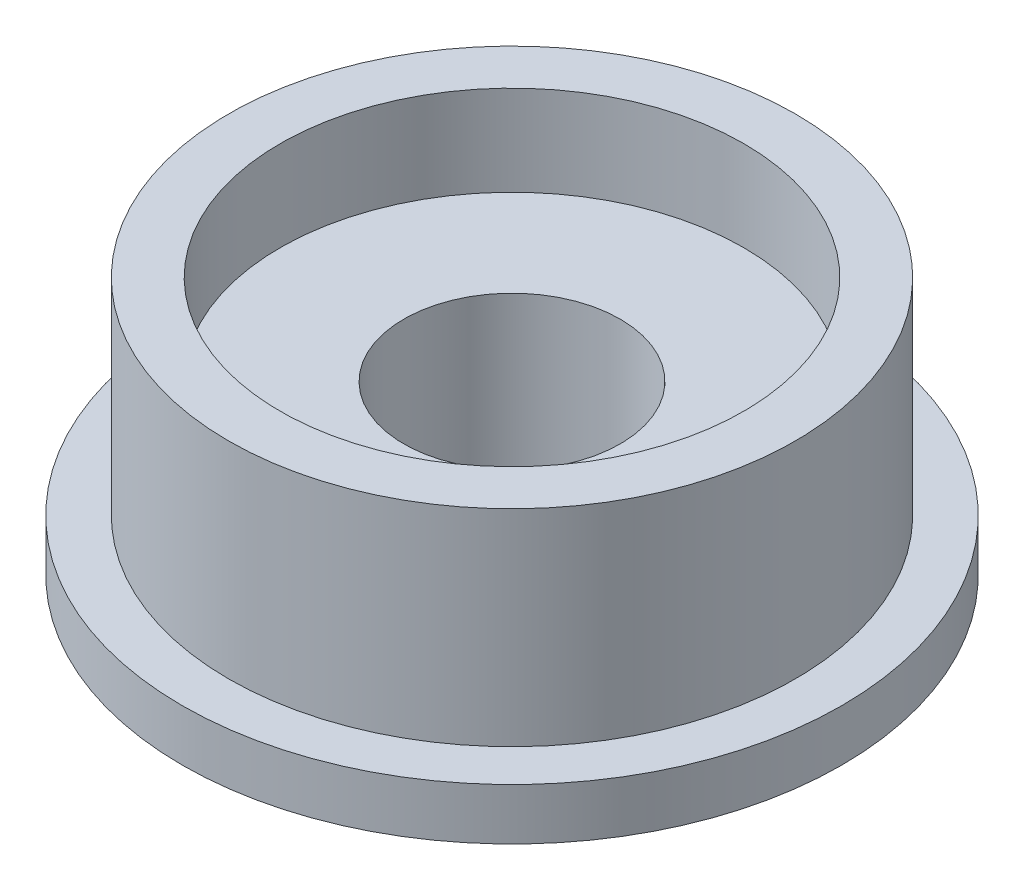
SolidWorks part; units mm, degrees
ref_plane "Front Plane" through (0, 0, 0) normal (0, 0, 1) x (1, 0, 0)
ref_plane "Top Plane" through (0, 0, 0) normal (0, 1, 0) x (1, 0, 0)
ref_plane "Right Plane" through (0, 0, 0) normal (1, 0, 0) x (0, 0, -1)
sketch "Sketch4" plane through (0, 0, 0) normal (0, 0, 1) x (1, 0, 0)
  line L0 (0, 0) -> (0, 12.0187) construction
  line L1 (4.2, 0) -> (4.2, 6.5)
  line L2 (4.2, 6.5) -> (9, 6.5)
  line L3 (9, 6.5) -> (9, 10)
  line L4 (9, 10) -> (11, 10)
  line L5 (11, 10) -> (11, 2)
  line L6 (11, 2) -> (12.8, 2)
  line L7 (12.8, 2) -> (12.8, 0)
  line L8 (4.2, 0) -> (12.8, 0)
  line L9 (0, 0) -> (4.2, 0) construction
  dimension "D1" = 25.6
  dimension "D2" = 8.4
  dimension "D3" = 18
  dimension "D4" = 22
  dimension "D5" = 6.5
  dimension "D6" = 3.5
  dimension "D7" = 2
  dimension "D8" = 2
revolve "Revolve1" add sketch "Sketch4" angle 360 about L0
